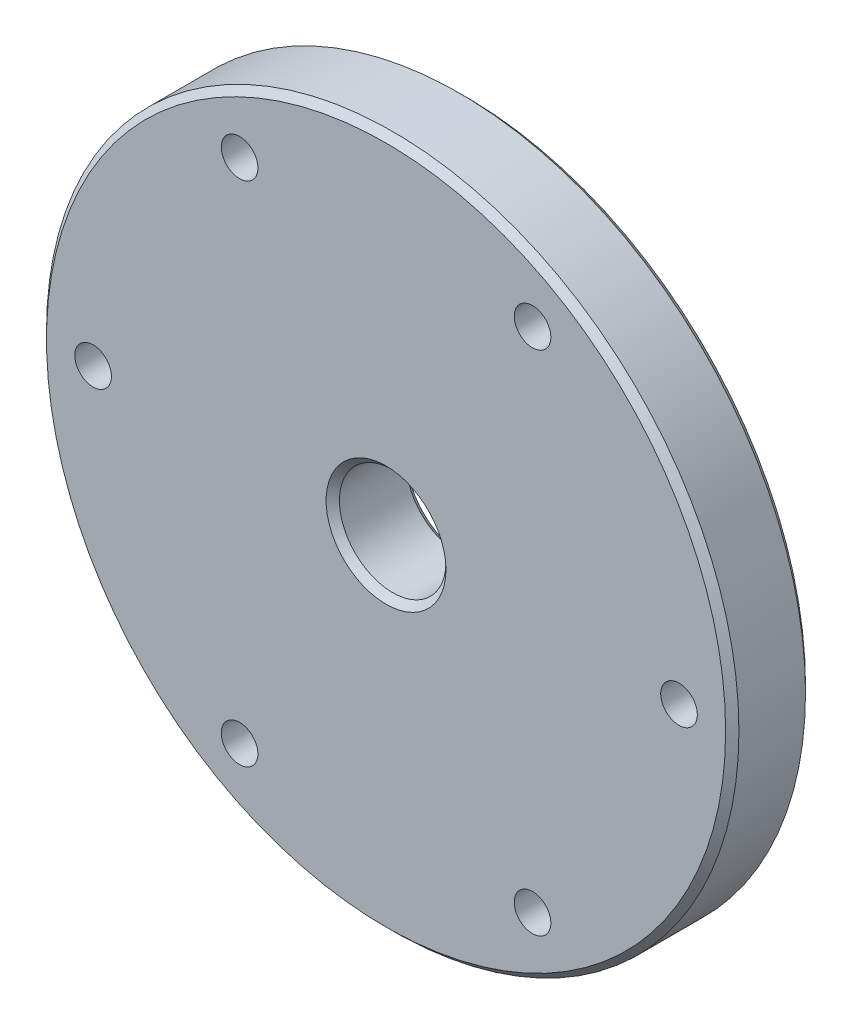
SolidWorks part; units mm, degrees
ref_plane "前视基准面" through (0, 0, 0) normal (0, 0, 1) x (1, 0, 0)
ref_plane "上视基准面" through (0, 0, 0) normal (0, 1, 0) x (1, 0, 0)
ref_plane "右视基准面" through (0, 0, 0) normal (1, 0, 0) x (0, 0, -1)
other "Configuration Table"
sketch "Sk_disc" plane through (0, 0, 0) normal (0, 0, 1) x (1, 0, 0)
  circle A0 centre (0, 0) radius 52
extrude "Ext_disc" add sketch "Sk_disc" along normal blind 12
sketch "Sk_c16" plane through (0, 0, 0) normal (0, 0, 1) x (1, 0, 0)
  circle A0 centre (0, 0) radius 8
extrude "Cut_c16" cut sketch "Sk_c16" along normal blind 12
chamfer "Chamfer_C1" distance 1 angle 45 4 edges at (8, 0, 0) (8, 0, 12) (52, 0, 0) (52, 0, 12)
sketch "Sk_bolt88" plane through (0, 0, 0) normal (0, 0, 1) x (1, 0, 0)
  circle A0 centre (44, 0) radius 2.75
  circle A1 centre (22, 38.1051) radius 2.75
  circle A2 centre (-22, 38.1051) radius 2.75
  circle A3 centre (-44, 0) radius 2.75
  circle A4 centre (-22, -38.1051) radius 2.75
  circle A5 centre (22, -38.1051) radius 2.75
extrude "Cut_bolt88" cut sketch "Sk_bolt88" along normal blind 12
sketch "Sk_seat" plane through (0, 0, 0) normal (0, 1, 0) x (1, 0, 0)
  line L0 (0, 0) -> (0, -20) construction
  line L1 (10, -4.0888) -> (10, 0)
  line L2 (10, 0) -> (20, 0)
  arc A0 (20, 0) -> (10, -4.0888) centre (0.0013, 34.6379) cw
revolve "Cut_seatR40" cut sketch "Sk_seat" angle 360 about L0
sketch "Sk_groove70" plane through (0, 0, 0) normal (0, 0, 1) x (1, 0, 0)
  circle A0 centre (0, 0) radius 33.1
  circle A1 centre (0, 0) radius 36.9
extrude "Cut_groove70" cut sketch "Sk_groove70" along normal blind 2.4
